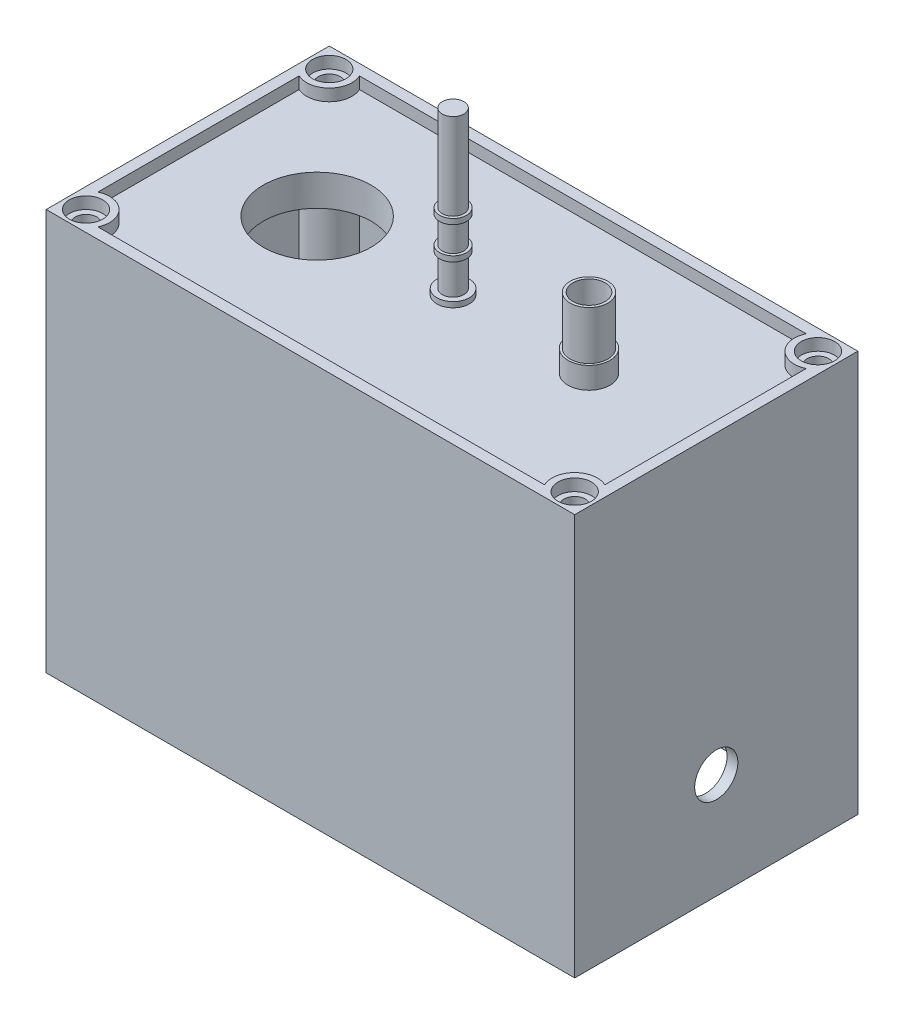
SolidWorks part; units mm, degrees
ref_plane "前视基准面" through (0, 0, 0) normal (0, 0, 1) x (1, 0, 0)
ref_plane "上视基准面" through (0, 0, 0) normal (0, 1, 0) x (1, 0, 0)
ref_plane "右视基准面" through (0, 0, 0) normal (1, 0, 0) x (0, 0, -1)
other "Configuration Table"
sketch "草图1" plane through (0, 0, 0) normal (0, 1, 0) x (1, 0, 0)
  line L1 (-24.5, -13.125) -> (24.5, -13.125)
  line L2 (-24.5, -13.125) -> (-24.5, 13.125)
  line L3 (-24.5, 13.125) -> (24.5, 13.125)
  line L4 (24.5, -13.125) -> (24.5, 13.125)
  line L5 (-24.5, -13.125) -> (24.5, 13.125) construction
  line L6 (-24.5, 13.125) -> (24.5, -13.125) construction
  point P0 (0, 0)
  dimension "D1" = 49
  dimension "D2" = 26.25
extrude "凸台-拉伸1" add sketch "草图1" along normal blind 5
sketch "草图2" plane through (0, 5, 0) normal (0, 1, 0) x (1, 0, 0)
  line L0 (24.5, 13.125) -> (-24.5, 13.125) construction
  line L1 (-24.5, 13.125) -> (-24.5, -13.125) construction
  line L2 (0, 0) -> (0, 50000) construction
  line L3 (0, 0) -> (-50000, 0) construction
  circle A0 centre (-22.65, 11.275) radius 1.55
  dimension "D1" = 3.1
  dimension "D2" = 1.85
  dimension "D3" = 1.85
extrude "切除-拉伸1" cut sketch "草图2" against normal blind 1.1
mirror "镜向1" about plane through (0, 0, 0) normal (1, 0, 0) of "切除-拉伸1"
mirror "镜向2" about plane through (0, 0, 0) normal (0, 0, 1) of "镜向1", "切除-拉伸1"
sketch "草图3" plane through (0, 5, 0) normal (0, 1, 0) x (1, 0, 0)
  line L0 (24.5, 13.125) -> (-24.5, 13.125) construction
  line L1 (-24.5, 13.125) -> (-24.5, -13.125) construction
  line L12 (0, 0) -> (0, 50000) construction
  line L13 (23.5, 0) -> (-50000, 0) construction
  line L19 (-23.5, -12.125) -> (23.5, -12.125)
  line L20 (23.5, -12.125) -> (23.5, 12.125)
  line L21 (23.5, 12.125) -> (-23.5, 12.125)
  line L22 (-23.5, 12.125) -> (-23.5, -12.125)
  line L23 (-20.7053, -12.125) -> (20.7053, -12.125)
  line L24 (23.5, -9.3303) -> (23.5, 9.3303)
  line L25 (20.7053, 12.125) -> (-20.7053, 12.125)
  line L26 (-23.5, 9.3303) -> (-23.5, -9.3303)
  arc A0 (-20.7053, 12.125) -> (-23.5, 9.3303) centre (-22.605, 11.23) cw
  arc A1 (20.7053, 12.125) -> (23.5, 9.3303) centre (22.605, 11.23) ccw
  arc A2 (20.7053, -12.125) -> (23.5, -9.3303) centre (22.605, -11.23) cw
  arc A3 (-20.7053, -12.125) -> (-23.5, -9.3303) centre (-22.605, -11.23) ccw
  point P0 (-21.7, 13.125)
  point P1 (-24.5, 10.325)
  dimension "D3" = 2.1
  dimension "D1" = 2.8
  dimension "D2" = 2.8
  dimension "D4" = 1
extrude "切除-拉伸2" cut sketch "草图3" against normal blind 1.1
sketch "草图4" plane through (0, 3.9, 0) normal (0, 1, 0) x (1, 0, 0)
  circle A0 centre (-22.65, 11.275) radius 1
  circle A1 centre (22.65, 11.275) radius 1
  circle A2 centre (22.65, -11.275) radius 1
  circle A3 centre (-22.65, -11.275) radius 1
  dimension "D1" = 2
extrude "切除-拉伸3" cut sketch "草图4" against normal blind 50
sketch "草图5" plane through (0, 3.9, 0) normal (0, 1, 0) x (1, 0, 0)
  line L1 (-23.5, 9.3303) -> (-23.5, -9.3303) construction
  circle A0 centre (-12.5, 0) radius 5
  dimension "D1" = 10
  dimension "D2" = 11
extrude "切除-拉伸4" cut sketch "草图5" against normal through all
sketch "草图6" plane through (0, 3.9, 0) normal (0, 1, 0) x (1, 0, 0)
  circle A0 centre (0.1, 0) radius 1.5
  circle A1 centre (0.1, 0) radius 1
  point P0 (-12.5, 0)
  dimension "D1" = 3
  dimension "D2" = 2
  dimension "D3" = 12.6
extrude "凸台-拉伸2" add sketch "草图6" along normal blind 0.5
sketch "草图10" plane through (0, 0, 0) normal (0, -1, 0) x (1, 0, 0)
  line L0 (23.5, 9.3303) -> (23.5, -9.3303) construction
  line L1 (-20.7053, 12.125) -> (20.7053, 12.125) construction
  line L2 (-23.5, -9.3303) -> (-23.5, 9.3303) construction
  line L3 (20.7053, -12.125) -> (-20.7053, -12.125) construction
  line L4 (23.5, 9.3303) -> (23.5, -9.3303)
  line L5 (-20.7053, 12.125) -> (20.7053, 12.125)
  line L6 (-23.5, -9.3303) -> (-23.5, 9.3303)
  line L7 (20.7053, -12.125) -> (-20.7053, -12.125)
  arc A0 (20.7053, 12.125) -> (23.5, 9.3303) centre (22.605, 11.23) ccw construction
  arc A1 (23.5, -9.3303) -> (20.7053, -12.125) centre (22.605, -11.23) ccw construction
  arc A2 (-20.7053, -12.125) -> (-23.5, -9.3303) centre (-22.605, -11.23) ccw construction
  arc A3 (20.7053, 12.125) -> (23.5, 9.3303) centre (22.605, 11.23) ccw
  arc A4 (23.5, -9.3303) -> (20.7053, -12.125) centre (22.605, -11.23) ccw
  arc A5 (-20.7053, -12.125) -> (-23.5, -9.3303) centre (-22.605, -11.23) ccw
  arc A6 (-23.5, 9.3303) -> (-20.7053, 12.125) centre (-22.605, 11.23) ccw construction
  arc A7 (-23.5, 9.3303) -> (-20.7053, 12.125) centre (-22.605, 11.23) ccw
extrude "切除-拉伸6" cut sketch "草图10" against normal blind 1
sketch "草图23" plane through (0, 3.9, 0) normal (0, 1, 0) x (1, 0, 0)
  circle A0 centre (12.7, 0) radius 1.5
  point P2 (0.1, 0)
  dimension "D2" = 3
  dimension "D1" = 12.6
extrude "切除-拉伸14" cut sketch "草图23" against normal through all
sketch "草图25" plane through (0, 3.9, 0) normal (0, 1, 0) x (1, 0, 0)
  circle A0 centre (12.7, 0) radius 1.5
  circle A1 centre (12.7, 0) radius 1.75
  dimension "D1" = 3.5
extrude "凸台-拉伸13" add sketch "草图25" along normal blind 6.5
sketch "草图26" plane through (0, 3.9, 0) normal (0, 1, 0) x (1, 0, 0)
  circle A0 centre (0.1, 0) radius 1
extrude "凸台-拉伸14" add sketch "草图26" along normal blind 15
ref_plane "基准面3" through (0, 10.4, 0) normal (0, 1, 0) x (1, 0, 0)
sketch "草图20" plane through (0, 10.4, 0) normal (0, 1, 0) x (1, 0, 0)
  circle A0 centre (0.1, 0) radius 1
  circle A1 centre (0.1, 0) radius 1.25
  dimension "D1" = 2.5
extrude "凸台-拉伸10" add sketch "草图20" along normal up to surface (0.5 mm away)
ref_plane "基准面4" through (0, 7.4, 0) normal (0, 1, 0) x (1, 0, 0)
sketch "草图27" plane through (0, 7.4, 0) normal (0, 1, 0) x (1, 0, 0)
  circle A0 centre (0.1, 0) radius 1
  circle A1 centre (0.1, 0) radius 1.25
extrude "凸台-拉伸15" add sketch "草图27" along normal up to surface (0.5 mm away)
sketch "草图28" plane through (0, 3.9, 0) normal (0, 1, 0) x (1, 0, 0)
  circle A0 centre (12.7, 0) radius 1.75
  circle A2 centre (12.7, 0) radius 1.95
  dimension "D1" = 0.2
extrude "凸台-拉伸16" add sketch "草图28" along normal up to surface (2 mm away)
sketch "草图30" plane through (0, 0, 0) normal (0, -1, 0) x (1, 0, 0)
  line L0 (-20.7053, 12.125) -> (20.7053, 12.125)
  line L1 (-24.5, 13.125) -> (24.5, 13.125)
  line L2 (-24.5, 13.125) -> (-24.5, -13.125)
  line L3 (-24.5, -13.125) -> (24.5, -13.125)
  line L4 (24.5, 13.125) -> (24.5, -13.125)
  line L5 (23.5, 9.3303) -> (23.5, -9.3303)
  line L6 (20.7053, -12.125) -> (-20.7053, -12.125)
  line L7 (-23.5, -9.3303) -> (-23.5, 9.3303)
  arc A0 (-23.5, 9.3303) -> (-20.7053, 12.125) centre (-22.605, 11.23) ccw construction
  arc A1 (-23.5, 9.3303) -> (-20.7053, 12.125) centre (-22.605, 11.23) ccw construction
  arc A2 (-23.5, 9.3303) -> (-20.7053, 12.125) centre (-22.65, 11.275) ccw
  arc A3 (20.7053, 12.125) -> (23.5, 9.3303) centre (22.65, 11.275) ccw
  arc A4 (23.5, -9.3303) -> (20.7053, -12.125) centre (22.65, -11.275) ccw
  arc A5 (23.5, -9.3303) -> (20.7053, -12.125) centre (22.605, -11.23) ccw construction
  arc A6 (-20.7053, -12.125) -> (-23.5, -9.3303) centre (-22.65, -11.275) ccw
extrude "凸台-拉伸17" add sketch "草图30" along normal blind 32.2
sketch "草图31" plane through (0, 0, 0) normal (0, 1, 0) x (1, 0, 0)
  circle A0 centre (22.65, 11.275) radius 1
extrude "切除-拉伸15" cut sketch "草图31" against normal through all
mirror "镜向3" about plane through (0, 0, 0) normal (1, 0, 0) of "切除-拉伸3"
sketch "草图32" plane through (24.5, 0, 0) normal (1, 0, 0) x (0, 0, -1)
  line L0 (13.125, -32.2) -> (-13.125, -32.2) construction
  circle A1 centre (0, -22.45) radius 2
  point P0 (0, -22.45)
  dimension "D1" = 9.75
  dimension "D2" = 4
extrude "切除-拉伸16" cut sketch "草图32" against normal up to next
